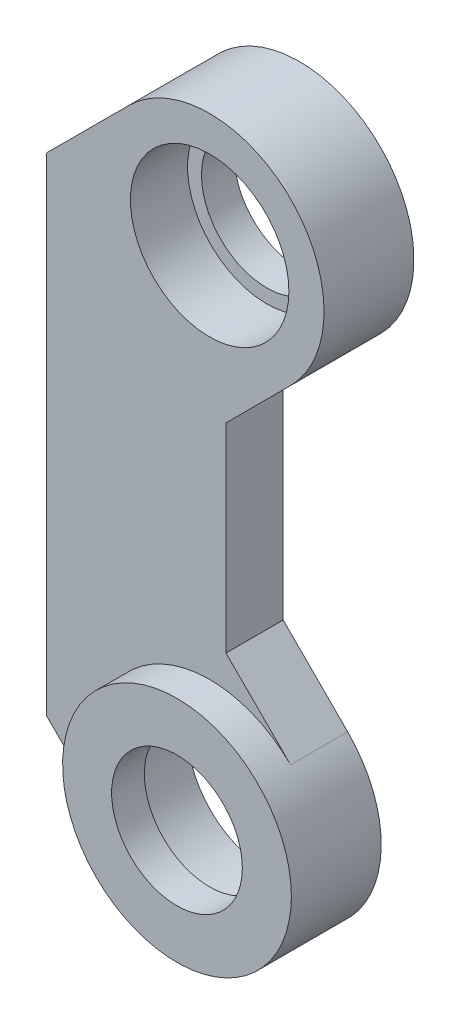
SolidWorks part; units mm, degrees
ref_plane "Alzado" through (0, 0, 0) normal (0, 0, 1) x (1, 0, 0)
ref_plane "Planta" through (0, 0, 0) normal (0, 1, 0) x (1, 0, 0)
ref_plane "Vista lateral" through (0, 0, 0) normal (1, 0, 0) x (0, 0, -1)
sketch "Croquis1" plane through (0, 0, 0) normal (0, 0, 1) x (1, 0, 0)
  line L0 (0, 0) -> (0, 30) construction
  line L1 (0, 0) -> (-6, 6) construction
  line L2 (-6, 6) -> (-6, 24) construction
  line L3 (-6, 24) -> (0, 30) construction
  line L4 (4.9497, 4.9497) -> (1, 8.8995)
  line L5 (1, 8.8995) -> (1, 21.1005)
  line L6 (1, 21.1005) -> (4.9497, 25.0503)
  line L7 (-4.9497, -4.9497) -> (-13, 3.1005)
  line L8 (-13, 3.1005) -> (-13, 26.8995)
  line L9 (-13, 26.8995) -> (-4.9497, 34.9497)
  circle A0 centre (0, 0) radius 4.85
  circle A1 centre (0, 0) radius 7
  circle A4 centre (0, 30) radius 4.85
  circle A5 centre (0, 30) radius 7
  dimension "D1" = 9.7
  dimension "D2" = 14
  dimension "D3" = 9.7
  dimension "D4" = 14
  dimension "D5" = 30
  dimension "D6" = 45
  dimension "D7" = 45
  dimension "D8" = 18
  dimension "D9" = 7
  dimension "D10" = 7
extrude "Saliente-Extruir1" add sketch "Croquis1" along normal blind 3.5 contours A5 L9 L8 L7 A1 L4 L5 L6 | A5 A4 | A1 A0
sketch "Croquis4" plane through (0, 0, 3.5) normal (0, 0, 1) x (1, 0, 0)
  line L0 (1, 15) -> (-13, 15)
  line L1 (1, 8.8995) -> (1, 21.1005) construction
  line L2 (-13, 3.1005) -> (-13, 26.8995) construction
  line L3 (-13, 26.8995) -> (-4.9497, 34.9497) construction
  line L4 (-10, 29.8995) -> (-18.2359, 29.8995)
  line L5 (-10, 29.8995) -> (-10, -2.6794)
  line L6 (-10, -2.6794) -> (-18.2359, -2.6794)
  line L7 (-18.2359, 29.8995) -> (-18.2359, -2.6794)
  dimension "D1" = 3
extrude "Cortar-Extruir4" cut sketch "Croquis4" against normal blind 4 contours L4 L7 L6 L5
sketch "Croquis5" plane through (0, 0, 3.5) normal (0, 0, 1) x (1, 0, 0)
  circle A0 centre (0, 0) radius 7
  circle A1 centre (0, 0) radius 4
  dimension "D1" = 8
extrude "Saliente-Extruir2" add sketch "Croquis5" along normal blind 2
sketch "Croquis6" plane through (0, 0, 0) normal (0, 0, -1) x (-1, 0, 0)
  line L0 (0, 25.15) -> (0, 30) construction
  circle A0 centre (0, 30) radius 4.85 construction
  circle A1 centre (0, 30) radius 7
  circle A2 centre (0, 30) radius 4
extrude "Saliente-Extruir3" add sketch "Croquis6" along normal blind 2
